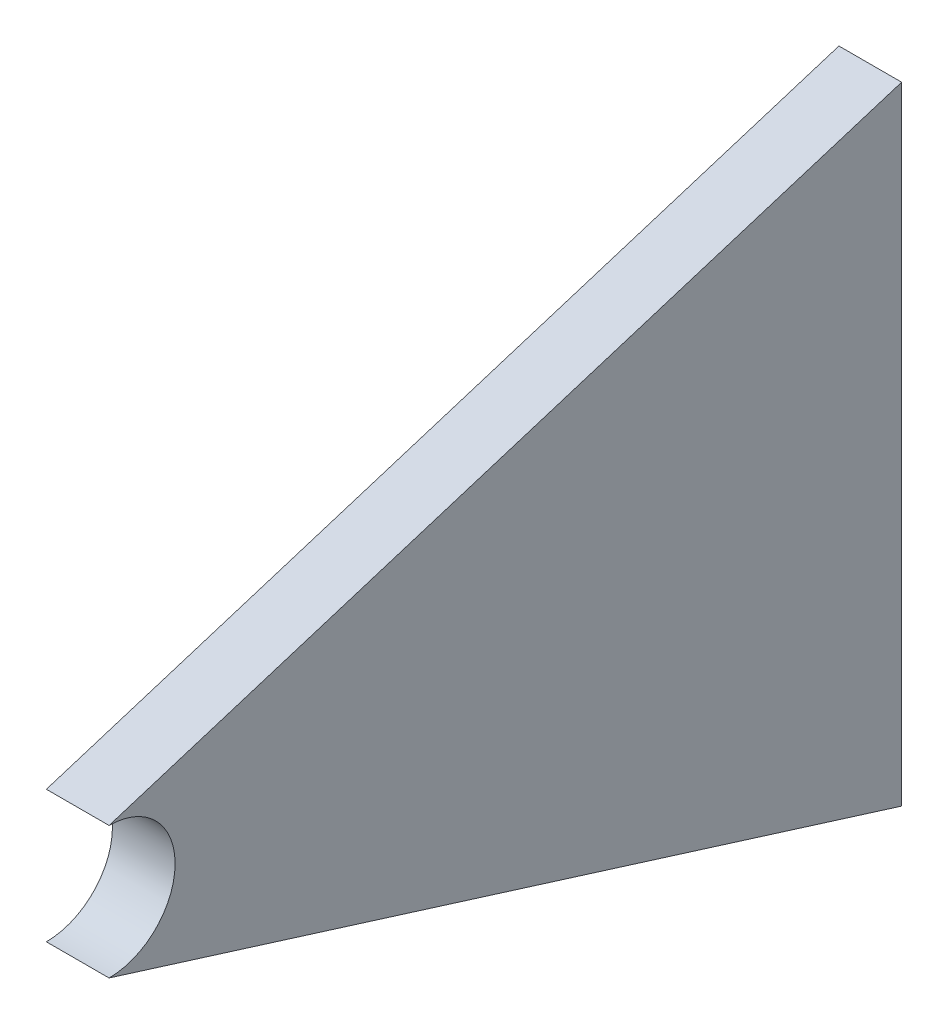
SolidWorks part; units mm, degrees
ref_plane "Front Plane" through (0, 0, 0) normal (1, 0, 0) x (0, 1, 0)
ref_plane "Top Plane" through (0, 0, 0) normal (0, 0, 1) x (0, 1, 0)
ref_plane "Right Plane" through (0, 0, 0) normal (0, 1, 0) x (-1, 0, 0)
sketch "Sketch1" plane through (0, 0, 0) normal (1, 0, 0) x (0, 1, 0)
  line L0 (0, -26.7254) -> (0, 99.6937) construction
  line L1 (23.4028, 99.6937) -> (-25.7868, 99.6937) construction
  line L2 (50, -26.7254) -> (-50, -26.7254)
  line L3 (-10.5349, 99.6937) -> (-50, -26.7254)
  line L4 (10.5349, 99.6937) -> (50, -26.7254)
  arc A0 (-10.5349, 99.6937) -> (10.5349, 99.6937) centre (0, 99.6937) ccw
  point P9 (0, -26.7254)
  dimension "D1" = 50
  dimension "D2" = 50
extrude "Boss-Extrude1" add sketch "Sketch1" along normal blind 10 contours L3 L2 L4 A0
